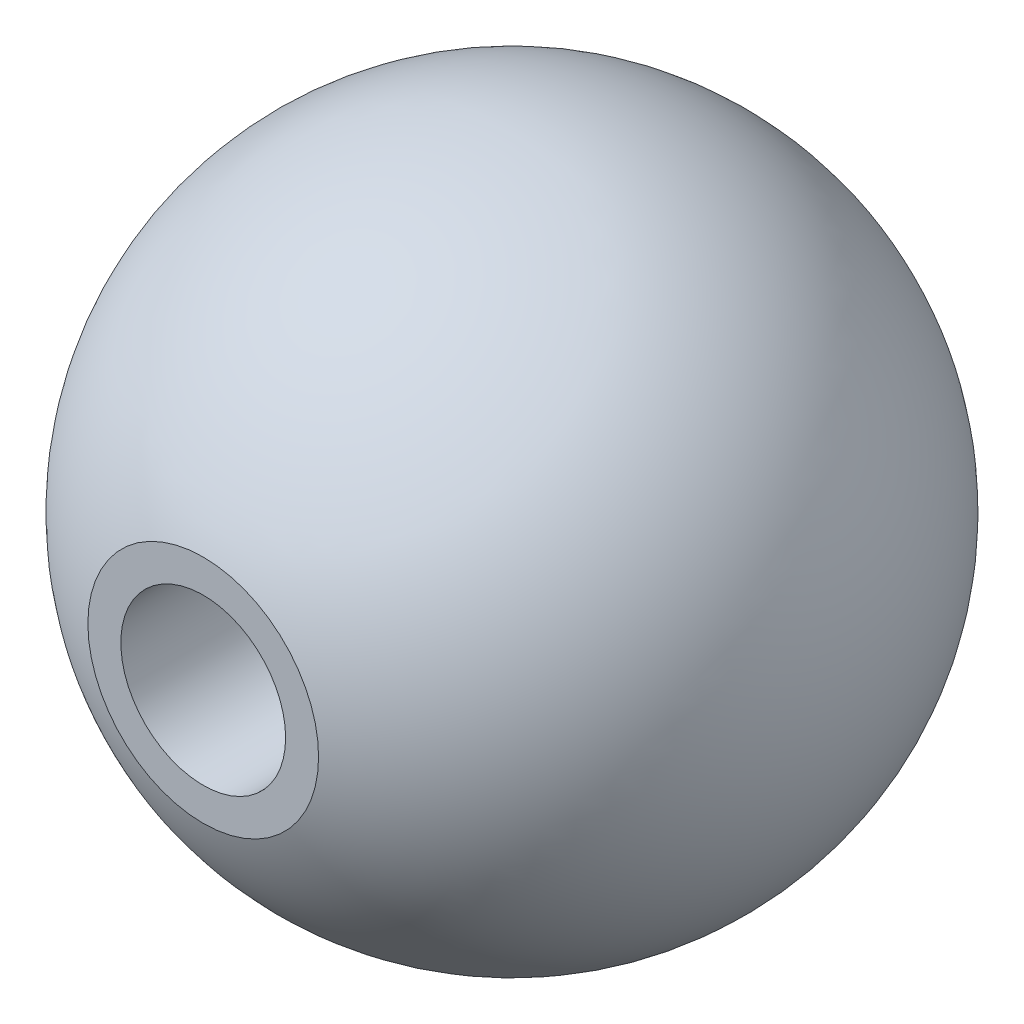
SolidWorks part; units mm, degrees
ref_plane "Front Plane" through (0, 0, 0) normal (0, 0, 1) x (1, 0, 0)
ref_plane "Top Plane" through (0, 0, 0) normal (0, 1, 0) x (1, 0, 0)
ref_plane "Right Plane" through (0, 0, 0) normal (1, 0, 0) x (0, 0, -1)
sketch "Sketch2" plane through (0, 0, 0) normal (0, 0, 1) x (1, 0, 0)
  line L0 (0, 0) -> (0, 12.7) construction
  line L3 (0, 12.7) -> (0, -12.7)
  line L4 (0, 0) -> (0, 12.7) construction
  arc A0 (0, -12.7) -> (0, 12.7) centre (0, 0) ccw
  dimension "D1" = 25.4
revolve "Revolve2" add sketch "Sketch2" angle 360 about L0
sketch "Sketch3" plane through (0, 0, 0) normal (0, 0, 1) x (1, 0, 0)
  circle A0 centre (0, 0) radius 4.445
  dimension "D1" = 8.89
extrude "Cut-Extrude1" cut sketch "Sketch3" along normal blind 2.54 from surface at 11.8967
sketch "Sketch4" plane through (0, 0, 11.8967) normal (0, 0, 1) x (1, 0, 0)
  circle A0 centre (0, 0) radius 3.175
  dimension "D1" = 6.35
extrude "Cut-Extrude2" cut sketch "Sketch4" against normal blind 7.62
mirror "Mirror1" about plane through (0, 0, 0) normal (0, 0, 1) of "Cut-Extrude2", "Cut-Extrude1"
